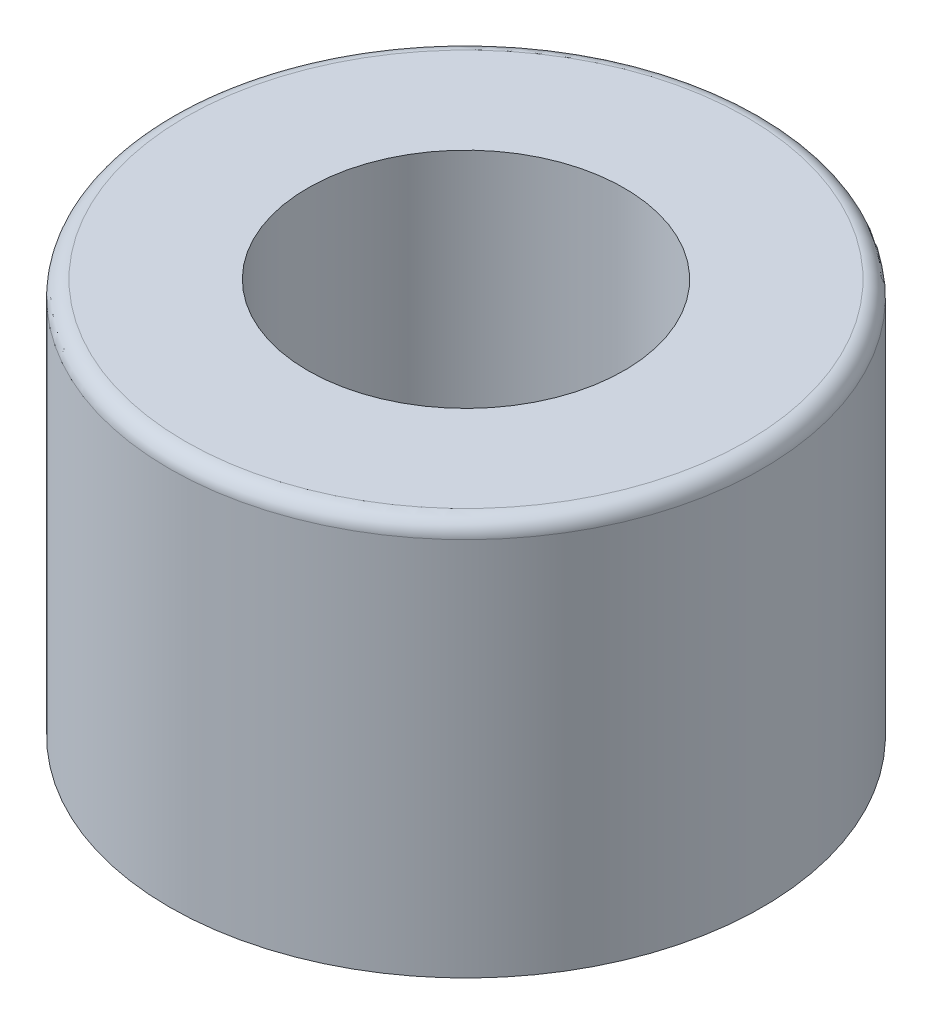
SolidWorks part; units mm, degrees
material "Nylon 6/10"
ref_plane "Front Plane" through (0, 0, 0) normal (0, 0, 1) x (1, 0, 0)
ref_plane "Top Plane" through (0, 0, 0) normal (0, 1, 0) x (1, 0, 0)
ref_plane "Right Plane" through (0, 0, 0) normal (1, 0, 0) x (0, 0, -1)
sketch "Sketch1" plane through (0, 0, 0) normal (0, 1, 0) x (1, 0, 0)
  circle A0 centre (0, 0) radius 4.7625
  circle A1 centre (0, 0) radius 2.54
  dimension "D1" = 5.08
  dimension "D2" = 9.525
extrude "Boss-Extrude1" add sketch "Sketch1" along normal blind 6.35
fillet "Fillet1" radius 0.254 1 edges at (0, 6.35, 4.7625)
